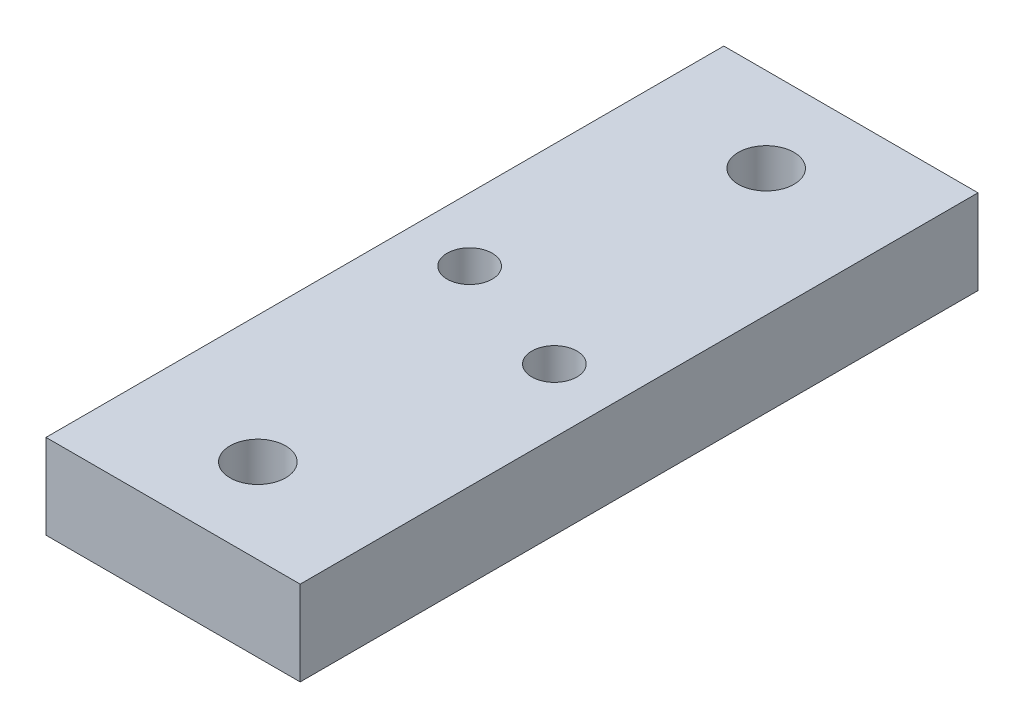
SolidWorks part; units mm, degrees
material "6061-T6 (SS)"
ref_plane "Front Plane" through (0, 0, 0) normal (0, 0, 1) x (1, 0, 0)
ref_plane "Top Plane" through (0, 0, 0) normal (0, 1, 0) x (1, 0, 0)
ref_plane "Right Plane" through (0, 0, 0) normal (1, 0, 0) x (0, 0, -1)
sketch "Sketch1" plane through (0, 0, 0) normal (0, 1, 0) x (1, 0, 0)
  line L1 (0, 0) -> (38.1, 0)
  line L2 (0, 0) -> (0, 101.6)
  line L3 (0, 101.6) -> (38.1, 101.6)
  line L4 (38.1, 0) -> (38.1, 101.6)
  circle A0 centre (19.05, 88.9) radius 4.1656
  circle A1 centre (19.05, 12.7) radius 4.1656
  dimension "D3" = 8.3312
  dimension "D4" = 8.3312
  dimension "D1" = 38.1
  dimension "D2" = 101.6
  dimension "D5" = 19.05
  dimension "D6" = 12.7
  dimension "D7" = 19.05
  dimension "D8" = 12.7
extrude "Boss-Extrude1" add sketch "Sketch1" along normal blind 12.7
hole_wizard "CBORE for 1/4 Hex Machine Screw1" positions "Sketch2" profile "Sketch3" counterbore size "1/4" standard "ANSI Inch" end condition through all
sketch "Sketch2" plane through (0, 0, 0) normal (0, -1, 0) x (-1, 0, 0)
  line L0 (0, 101.6) -> (0, 0) construction
  point P0 (-28.575, 47.625)
  point P2 (-9.525, 53.975)
  dimension "D1" = 9.525
  dimension "D2" = 47.625
  dimension "D3" = 9.525
  dimension "D4" = 47.625
sketch "Sketch3" plane through (28.575, 0, -47.625) normal (1, 0, 0) x (0, 0, -1)
  line L0 (0, 0) -> (0, 12.7)
  line L1 (0, 12.7) -> (3.3782, 12.7)
  line L3 (3.3782, 12.7) -> (3.3782, 4.826)
  line L4 (3.3782, 4.826) -> (7.9375, 4.826)
  line L5 (7.9375, 4.826) -> (7.9375, 0)
  line L7 (7.9375, 0) -> (0, 0)
  line L11 (0, -6.35) -> (0, 107.95) construction
  dimension "Thru Hole Dia." = 6.7564
  dimension "Thru Hole Depth" = 12.7
  dimension "C'Bore Dia." = 15.875
  dimension "C'Bore Depth" = 4.826
